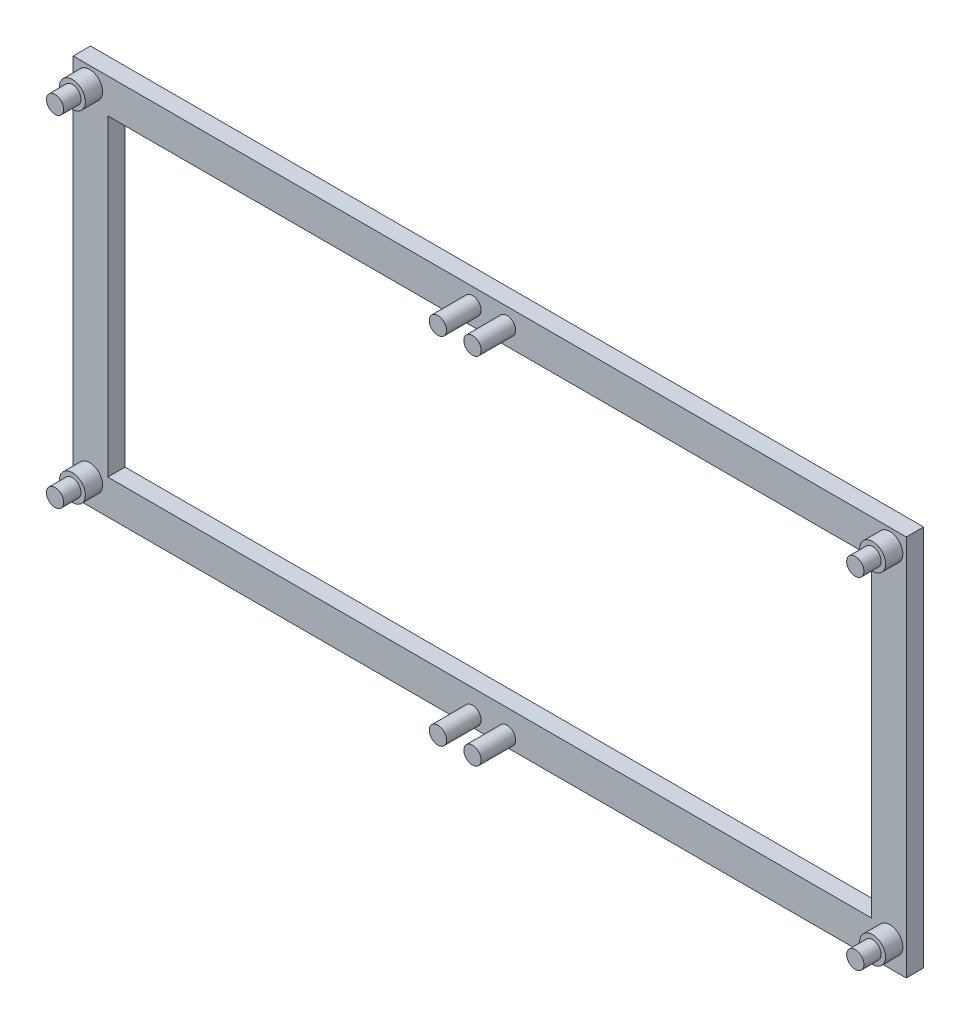
SolidWorks part; units mm, degrees
ref_plane "Front Plane" through (0, 0, 0) normal (0, 0, 1) x (1, 0, 0)
ref_plane "Top Plane" through (0, 0, 0) normal (0, 1, 0) x (1, 0, 0)
ref_plane "Right Plane" through (0, 0, 0) normal (1, 0, 0) x (0, 0, -1)
sketch "Sketch1" plane through (0, 0, 0) normal (0, 0, 1) x (1, 0, 0)
  line L1 (48.2, -22.1) -> (-48.2, -22.1)
  line L2 (48.2, -22.1) -> (48.2, 22.1)
  line L3 (48.2, 22.1) -> (-48.2, 22.1)
  line L4 (-48.2, -22.1) -> (-48.2, 22.1)
  line L5 (48.2, -22.1) -> (-48.2, 22.1) construction
  line L6 (48.2, 22.1) -> (-48.2, -22.1) construction
  line L7 (44.2, -18.1) -> (-44.2, -18.1)
  line L8 (44.2, -18.1) -> (44.2, 18.1)
  line L9 (44.2, 18.1) -> (-44.2, 18.1)
  line L10 (-44.2, -18.1) -> (-44.2, 18.1)
  line L11 (44.2, -18.1) -> (-44.2, 18.1) construction
  line L12 (44.2, 18.1) -> (-44.2, -18.1) construction
  point P0 (0, 0)
  point P6 (0, 0)
  dimension "D1" = 96.4
  dimension "D2" = 44.2
  dimension "D3" = 4
  dimension "D4" = 4
extrude "Boss-Extrude1" add sketch "Sketch1" along normal blind 2
sketch "Sketch2" plane through (0, 0, 2) normal (0, 0, 1) x (1, 0, 0)
  line L0 (48.2, 22.1) -> (-48.2, 22.1) construction
  line L1 (-48.2, 22.1) -> (-48.2, -22.1) construction
  line L2 (-48.2, -22.1) -> (48.2, -22.1) construction
  line L3 (48.2, -22.1) -> (48.2, 22.1) construction
  circle A0 centre (-46.3, 20.2) radius 1
  circle A1 centre (-46.3, -19.2) radius 1
  circle A2 centre (46.3, -19.2) radius 1
  circle A3 centre (46.3, 20.2) radius 1
  circle A4 centre (-2, 20.2) radius 1
  circle A5 centre (-2, -20.8624) radius 1
  circle A6 centre (2, 20.2) radius 1
  circle A7 centre (2, -20.8624) radius 1
  dimension "D3" = 2
  dimension "D10" = 2
  dimension "D11" = 2
  dimension "D12" = 2
  dimension "D15" = 2
  dimension "D16" = 2
  dimension "D18" = 2
  dimension "D20" = 2
  dimension "D1" = 1.9
  dimension "D2" = 1.9
  dimension "D4" = 1.9
  dimension "D5" = 2.9
  dimension "D6" = 2.9
  dimension "D7" = 1.9
  dimension "D8" = 1.9
  dimension "D9" = 1.9
  dimension "D13" = 44.3
  dimension "D14" = 44.3
  dimension "D17" = 44.3
  dimension "D19" = 44.3
  dimension "D21" = 4
extrude "Boss-Extrude2" add sketch "Sketch2" along normal blind 4
sketch "Sketch3" plane through (0, 0, 2) normal (0, 0, 1) x (1, 0, 0)
  circle A0 centre (-46.3, 20.2) radius 1.5
  circle A1 centre (-46.3, -19.2) radius 1.5
  circle A2 centre (46.3, -19.2) radius 1.5
  circle A3 centre (46.3, 20.2) radius 1.5
  dimension "D1" = 3
  dimension "D2" = 3
  dimension "D3" = 3
  dimension "D4" = 3
extrude "Boss-Extrude3" add sketch "Sketch3" along normal blind 2
